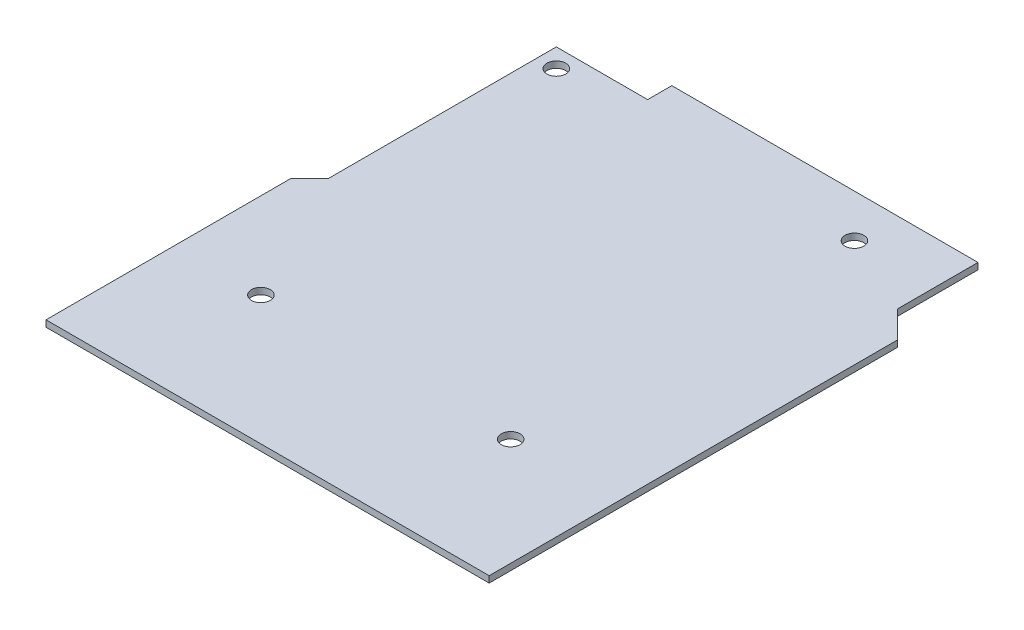
SolidWorks part; units mm, degrees
ref_plane "Front Plane" through (0, 0, 0) normal (0, 0, 1) x (1, 0, 0)
ref_plane "Top Plane" through (0, 0, 0) normal (0, 1, 0) x (1, 0, 0)
ref_plane "Right Plane" through (0, 0, 0) normal (1, 0, 0) x (0, 0, -1)
sketch "Sketch1" plane through (0, 0, 0) normal (0, 1, 0) x (1, 0, 0)
  line L0 (0, 0) -> (0, 45.5)
  line L1 (0, 45.5) -> (3.5, 49)
  line L2 (3.5, 49) -> (3.5, 91.5)
  line L3 (3.5, 91.5) -> (20.5, 91.5)
  line L4 (20.5, 91.5) -> (20.5, 96)
  line L5 (20.5, 96) -> (77.5, 96)
  line L6 (77.5, 96) -> (77.5, 81)
  line L7 (77.5, 81) -> (82.5, 76)
  line L8 (82.5, 76) -> (82.5, 0)
  line L9 (82.5, 0) -> (0, 0)
  circle A0 centre (7, 88) radius 1.75
  circle A1 centre (62.5, 88) radius 1.75
  circle A2 centre (62.5, 24) radius 1.75
  circle A3 centre (16, 24) radius 1.75
  point P19 (0, 0)
  point P20 (0, 0)
  point P23 (0, 0)
  dimension "D11" = 3.5
  dimension "D1" = 82.5
  dimension "D2" = 96
  dimension "D3" = 45.5
  dimension "D4" = 49
  dimension "D5" = 3.5
  dimension "D6" = 91.5
  dimension "D7" = 17
  dimension "D8" = 57
  dimension "D9" = 15
  dimension "D10" = 76
  dimension "D12" = 24
  dimension "D13" = 16
  dimension "D14" = 62.5
  dimension "D15" = 7
  dimension "D16" = 8
  dimension "D17" = 62.5
extrude "PCB" add sketch "Sketch1" along normal blind 1.2
